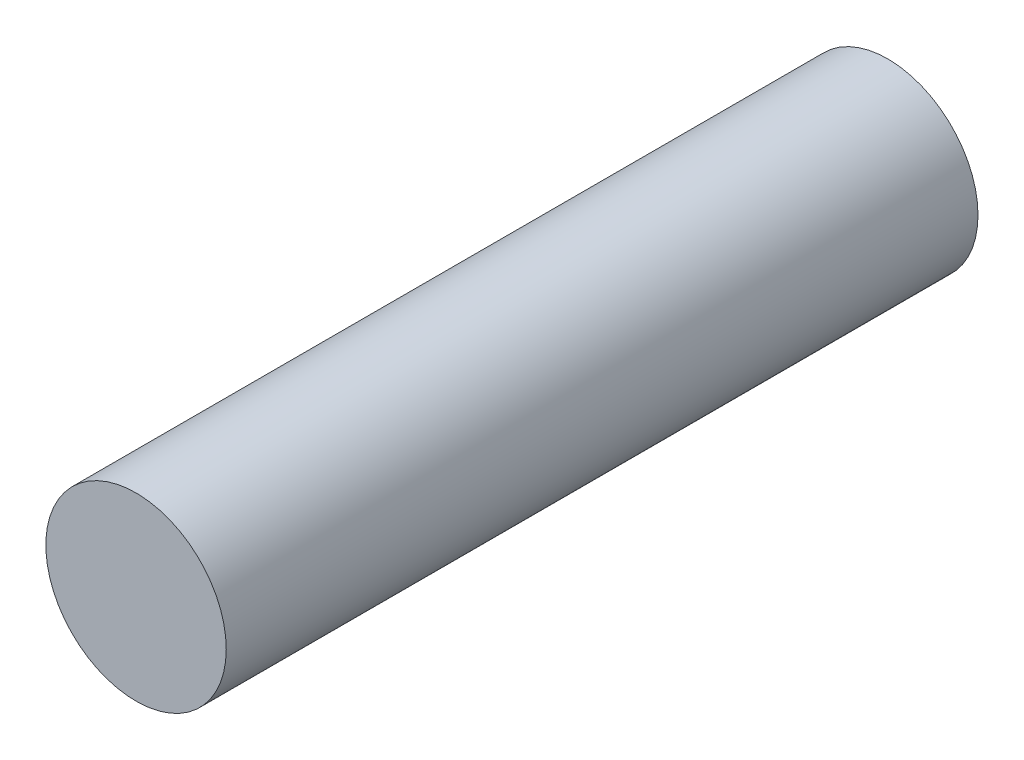
SolidWorks part; units mm, degrees
material "Plain Carbon Steel"
ref_plane "Front Plane" through (0, 0, 0) normal (0, 0, 1) x (1, 0, 0)
ref_plane "Top Plane" through (0, 0, 0) normal (0, 1, 0) x (1, 0, 0)
ref_plane "Right Plane" through (0, 0, 0) normal (1, 0, 0) x (0, 0, -1)
sketch "Sketch1" plane through (0, 0, 0) normal (0, 0, 1) x (1, 0, 0)
  circle A0 centre (0, 0) radius 12
  dimension "D1" = 24
extrude "Boss-Extrude1" add sketch "Sketch1" along normal blind 100
